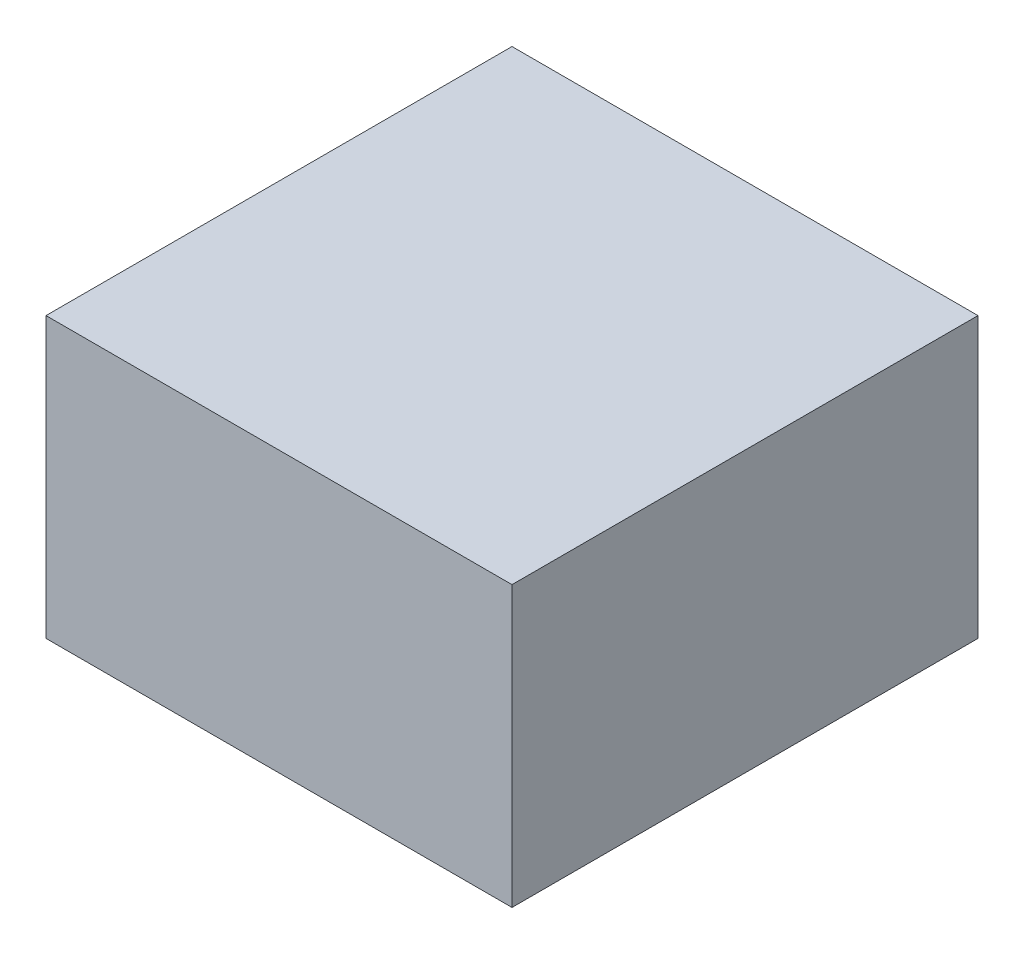
SolidWorks part; units mm, degrees
ref_plane "Front Plane" through (0, 0, 0) normal (0, 0, 1) x (1, 0, 0)
ref_plane "Top Plane" through (0, 0, 0) normal (0, 1, 0) x (1, 0, 0)
ref_plane "Right Plane" through (0, 0, 0) normal (1, 0, 0) x (0, 0, -1)
sketch "Sketch1" plane through (0, 0, 0) normal (0, 1, 0) x (1, 0, 0)
  line L1 (6.35, 6.35) -> (-6.35, 6.35)
  line L2 (6.35, 6.35) -> (6.35, -6.35)
  line L3 (6.35, -6.35) -> (-6.35, -6.35)
  line L4 (-6.35, 6.35) -> (-6.35, -6.35)
  line L5 (6.35, 6.35) -> (-6.35, -6.35) construction
  line L6 (6.35, -6.35) -> (-6.35, 6.35) construction
  point P0 (0, 0)
  dimension "D1" = 12.7
  dimension "D2" = 12.7
extrude "Boss-Extrude1" add sketch "Sketch1" along normal blind 7.62
